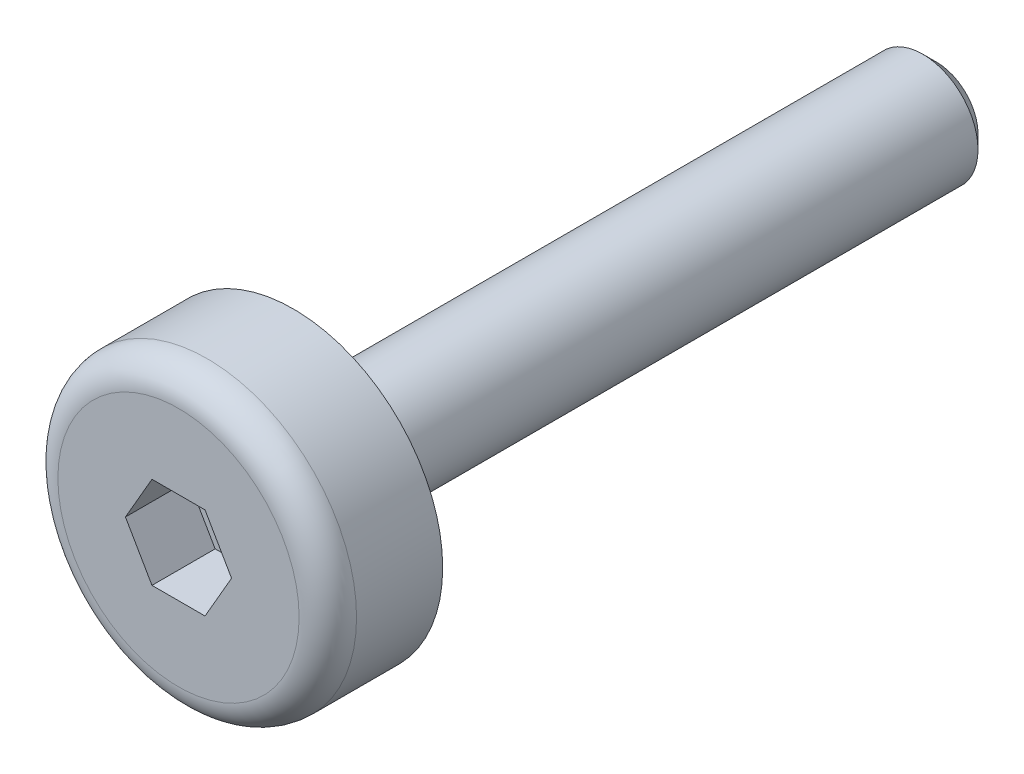
SolidWorks part; units mm, degrees
ref_plane "Front Plane" through (0, 0, 0) normal (0, 0, 1) x (1, 0, 0)
ref_plane "Top Plane" through (0, 0, 0) normal (0, 1, 0) x (1, 0, 0)
ref_plane "Right Plane" through (0, 0, 0) normal (1, 0, 0) x (0, 0, -1)
sketch "Screw Section" plane through (0, 0, 0) normal (0, 1, 0) x (1, 0, 0)
  line L0 (0, 14) -> (1.2, 14)
  line L1 (1.2, 14) -> (1.2, 0)
  line L2 (1.2, 0) -> (3.25, 0)
  line L3 (3.25, 0) -> (3.25, -2.5)
  line L4 (3.25, -2.5) -> (0, -2.5)
  line L5 (0, -2.5) -> (0, 14)
  line L6 (0, -10.123) -> (0, 10.123) construction
  dimension "D1" = 1.2
  dimension "D2" = 3.25
  dimension "D3" = 14
  dimension "D4" = 2.5
  dimension "D5" = 10.123
  dimension "D6" = 10.123
revolve "Screw Blank Revolve" add sketch "Screw Section" angle 360 about L6
chamfer "Shank Tip Chamfer" distance 0.3 1 edges at (1.2, 0, -14)
fillet "Pan Head Round" radius 0.625 1 edges at (3.25, 0, 2.5)
ref_plane "Head Crown Plane" through (0, 0, 2.5) normal (0, 0, 1) x (1, 0, 0)
sketch "Hex Drive Sketch" plane through (0, 0, 2.5) normal (0, 0, 1) x (1, 0, 0)
  line L1 (1.1547, 0) -> (0.5774, 1)
  line L2 (0.5774, 1) -> (-0.5774, 1)
  line L3 (-0.5774, 1) -> (-1.1547, 0)
  line L4 (-1.1547, 0) -> (-0.5774, -1)
  line L5 (-0.5774, -1) -> (0.5774, -1)
  line L6 (0.5774, -1) -> (1.1547, 0)
  circle A0 centre (0, 0) radius 1 construction
  dimension "D1" = 2
extrude "Hex Drive Cut" cut sketch "Hex Drive Sketch" against normal blind 1.375
equation "\"nominal_length\"= 14.0mm 'Screw length: under pan head or including flat head"
equation "\"model_shank_radius\"= 1.2mm 'Clearance envelope minor shank radius; thread is not modeled"
equation "\"head_diameter\"= 6.5mm 'Head outside diameter"
equation "\"head_height\"= 2.5mm 'Head axial height"
equation "\"drive_across_flats\"= 2mm 'Hex drive across flats"
equation "\"tip_chamfer\"= 0.3mm 'Shank tip chamfer"
equation "\"head_round\"= 0.625mm 'Pan head crown edge radius"
equation "\"drive_depth\"= 1.375mm 'Hex socket depth"
equation "\"axis_reference_halfspan\"= 10.123mm 'Half display length of the construction axis; avoids sharing a profile endpoint"
equation "\"D1@Screw Section\"= \"model_shank_radius\""
equation "\"D2@Screw Section\"= \"head_diameter\" / 2"
equation "\"D3@Screw Section\"= \"nominal_length\""
equation "\"D4@Screw Section\"= \"head_height\""
equation "\"D5@Screw Section\"= \"axis_reference_halfspan\""
equation "\"D6@Screw Section\"= \"axis_reference_halfspan\""
equation "\"full_turn\"= 360deg 'Full circular extent for revolves and patterns"
equation "\"D1@Screw Blank Revolve\"= \"full_turn\""
equation "\"D1@Shank Tip Chamfer\"= \"tip_chamfer\""
equation "\"D1@Pan Head Round\"= \"head_round\""
equation "\"D1@Head Crown Plane\"= \"head_height\""
equation "\"D1@Hex Drive Sketch\"= \"drive_across_flats\""
equation "\"D1@Hex Drive Cut\"= \"drive_depth\""
